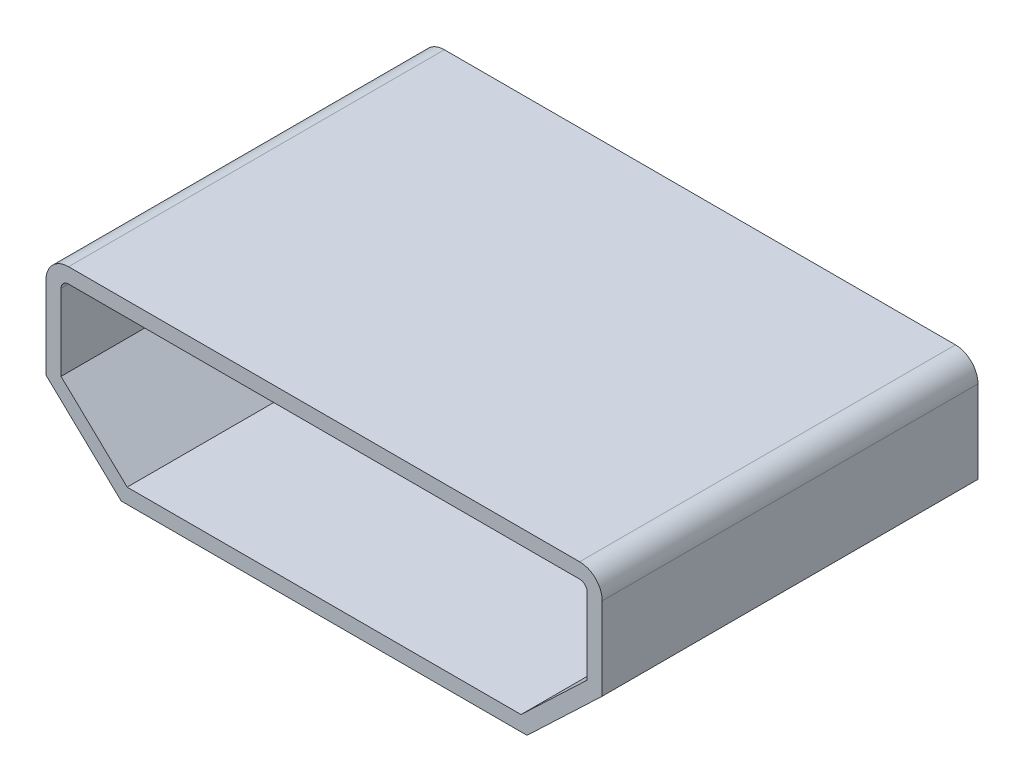
SolidWorks part; units mm, degrees
ref_plane "Спереди" through (0, 0, 0) normal (0, 0, 1) x (1, 0, 0)
ref_plane "Сверху" through (0, 0, 0) normal (0, 1, 0) x (1, 0, 0)
ref_plane "Справа" through (0, 0, 0) normal (1, 0, 0) x (0, 0, -1)
sketch "Sketch1" plane through (0, 0, 0) normal (0, 1, 0) x (1, 0, 0)
  line L1 (-3.7, -2.5) -> (3.7, -2.5)
  line L2 (-3.7, -2.5) -> (-3.7, 2.5)
  line L3 (-3.7, 2.5) -> (3.7, 2.5)
  line L4 (3.7, -2.5) -> (3.7, 2.5)
  line L5 (-3.7, -2.5) -> (3.7, 2.5) construction
  line L6 (-3.7, 2.5) -> (3.7, -2.5) construction
  point P0 (0, 0)
  dimension "D1" = 5
  dimension "D2" = 7.4
extrude "Boss-Extrude1" add sketch "Sketch1" along normal blind 2.35
sketch "Sketch2" plane through (0, 0, 2.5) normal (0, 0, 1) x (1, 0, 0)
  line L0 (3.7, 0) -> (2.7, 0)
  line L5 (-3.7, 0) -> (3.7, 0) construction
  line L6 (-2.7, 0) -> (-3.7, 0.95)
  line L7 (-3.7, 2.35) -> (-3.7, 0) construction
  line L8 (0, 2.6866) -> (0, -1.4865) construction
  line L9 (-3.7, 2.05) -> (-3.7, 2.35)
  line L12 (-3.7, 2.35) -> (-3.4, 2.35)
  line L13 (-3.7, 0.95) -> (-3.7, 0)
  line L14 (-3.7, 0) -> (-2.7, 0)
  line L15 (3.7, 0.95) -> (3.7, 0)
  line L16 (3.7, 2.35) -> (3.4, 2.35)
  line L17 (3.7, 2.05) -> (3.7, 2.35)
  line L18 (2.7, 0) -> (3.7, 0.95)
  arc A0 (-3.7, 2.05) -> (-3.4, 2.35) centre (-3.4, 2.05) cw
  arc A1 (3.7, 2.05) -> (3.4, 2.35) centre (3.4, 2.05) ccw
  point P18 (-3.7, 2.35)
  point P27 (3.7, 2.35)
  dimension "D2" = 0.3
  dimension "D3" = 1.1
extrude "Cut-Extrude1" cut sketch "Sketch2" against normal through all
sketch "Sketch3" plane through (0, 0, 2.5) normal (0, 0, 1) x (1, 0, 0)
  line L12 (3.5, 2.05) -> (3.5, 1.0359)
  line L13 (3.5, 1.0359) -> (2.6201, 0.2)
  line L14 (-2.6201, 0.2) -> (2.6201, 0.2)
  line L15 (-2.6201, 0.2) -> (-3.5, 1.0359)
  line L16 (-3.5, 2.05) -> (-3.5, 1.0359)
  line L17 (-3.4, 2.15) -> (3.4, 2.15)
  arc A4 (-3.4, 2.15) -> (-3.5, 2.05) centre (-3.4, 2.05) ccw
  arc A5 (3.5, 2.05) -> (3.4, 2.15) centre (3.4, 2.05) ccw
extrude "Cut-Extrude2" cut sketch "Sketch3" against normal blind 4.7
